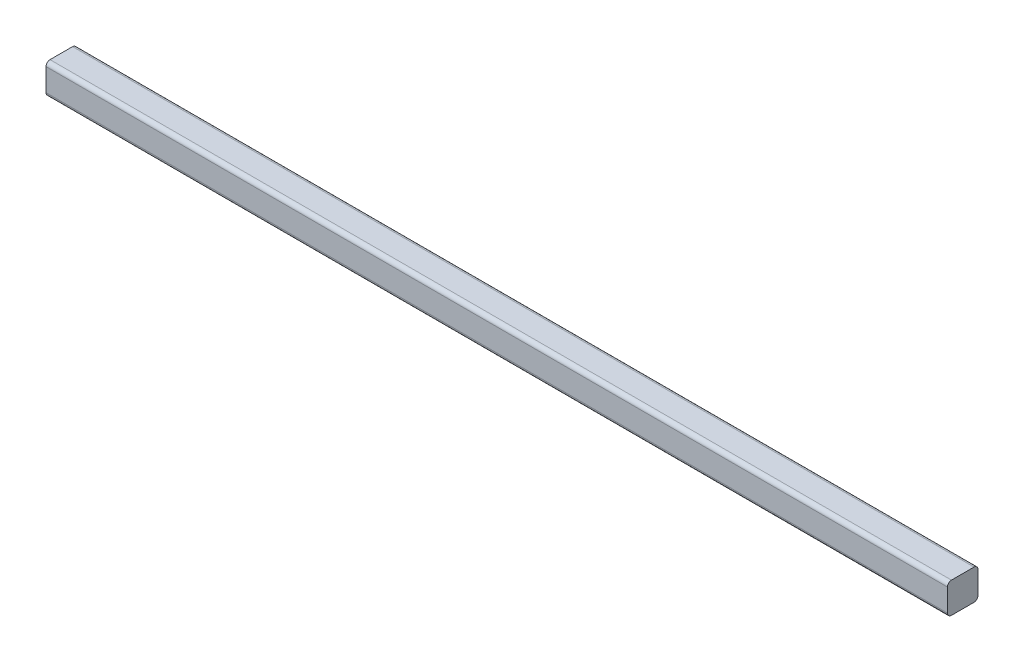
SolidWorks part; units mm, degrees
ref_plane "Front Plane" through (0, 0, 0) normal (0, 0, 1) x (1, 0, 0)
ref_plane "Top Plane" through (0, 0, 0) normal (0, 1, 0) x (1, 0, 0)
ref_plane "Right Plane" through (0, 0, 0) normal (1, 0, 0) x (0, 0, -1)
other "Configuration Table"
sketch "Sketch1" plane through (0, 0, 0) normal (1, 0, 0) x (0, 0, -1)
  line L1 (-19.05, -19.05) -> (19.05, -19.05)
  line L2 (-19.05, -19.05) -> (-19.05, 19.05)
  line L3 (-19.05, 19.05) -> (19.05, 19.05)
  line L4 (19.05, -19.05) -> (19.05, 19.05)
  line L5 (-19.05, -19.05) -> (19.05, 19.05) construction
  line L6 (-19.05, 19.05) -> (19.05, -19.05) construction
  point P0 (0, 0)
  dimension "D1" = 38.1
extrude "Boss-Extrude1" add sketch "Sketch1" along normal mid plane 1123.95
fillet "Fillet1" radius 5 4 edges at (0, -19.05, 19.05) (0, 19.05, 19.05) (0, -19.05, -19.05) (0, 19.05, -19.05)
